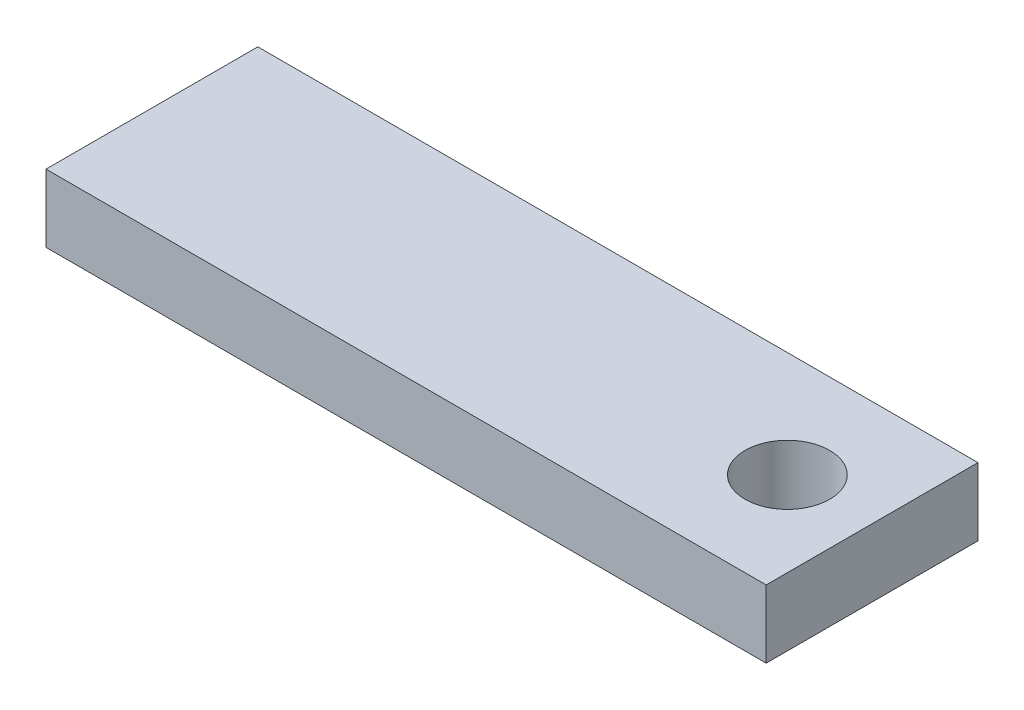
SolidWorks part; units mm, degrees
ref_plane "Plan de face" through (0, 0, 0) normal (0, 0, 1) x (1, 0, 0)
ref_plane "Plan de dessus" through (0, 0, 0) normal (0, 1, 0) x (1, 0, 0)
ref_plane "Plan de droite" through (0, 0, 0) normal (1, 0, 0) x (0, 0, -1)
sketch "Esquisse1" plane through (0, 0, 0) normal (0, 1, 0) x (1, 0, 0)
  line L0 (0, 2.5) -> (17, 2.5) construction
  line L1 (0, 5) -> (17, 5)
  line L2 (0, 5) -> (0, 0)
  line L3 (0, 0) -> (17, 0)
  line L4 (17, 5) -> (17, 0)
  circle A0 centre (15, 2.5) radius 1
  dimension "D3" = 2
  dimension "D1" = 17
  dimension "D2" = 5
  dimension "D4" = 2
extrude "Boss.-Extru.1" add sketch "Esquisse1" along normal blind 1.6
